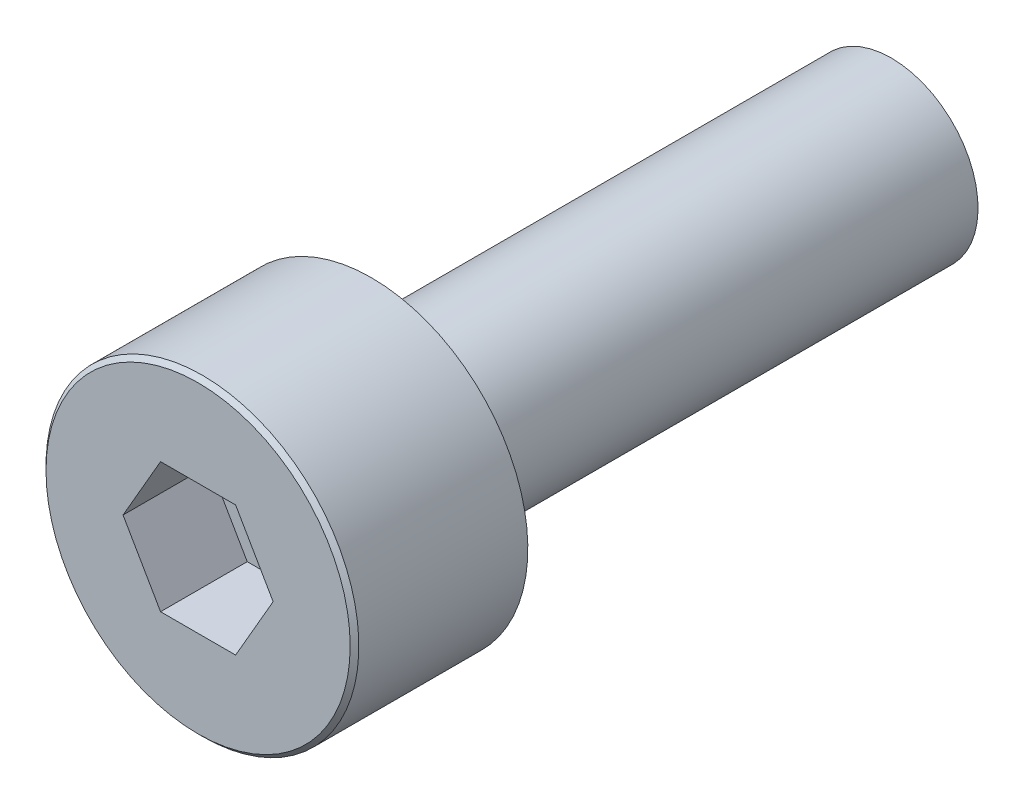
SolidWorks part; units mm, degrees
material "普通碳钢"
ref_plane "前视基准面" through (0, 0, 0) normal (0, 0, 1) x (1, 0, 0)
ref_plane "上视基准面" through (0, 0, 0) normal (0, 1, 0) x (1, 0, 0)
ref_plane "右视基准面" through (0, 0, 0) normal (1, 0, 0) x (0, 0, -1)
sketch "草图1" plane through (0, 0, 0) normal (1, 0, 0) x (0, 0, -1)
  line L0 (0, 0) -> (0, 3.61)
  line L1 (0, 3.61) -> (4, 3.61)
  line L2 (4, 3.61) -> (4, 2)
  line L3 (4, 2) -> (16, 2)
  line L4 (16, 2) -> (16, 0)
  line L5 (16, 0) -> (0, 0) construction
  line L6 (0, 0) -> (16, 0)
  dimension "D1" = 7.22
  dimension "D2" = 4
  dimension "D3" = 4
  dimension "D4" = 12
revolve "旋转1" add sketch "草图1" angle 360 about L5
cosmetic thread "装饰螺纹线1" parameters "D2"=2.459
sketch "草图2" plane through (0, 0, 0) normal (0, 0, 1) x (1, 0, 0)
  line L1 (0.866, 1.5) -> (-0.866, 1.5)
  line L2 (-0.866, 1.5) -> (-1.7321, 0)
  line L3 (-1.7321, 0) -> (-0.866, -1.5)
  line L4 (-0.866, -1.5) -> (0.866, -1.5)
  line L5 (0.866, -1.5) -> (1.7321, 0)
  line L6 (1.7321, 0) -> (0.866, 1.5)
  circle A0 centre (0, 0) radius 1.5 construction
  dimension "D1" = 3
extrude "切除-拉伸1" cut sketch "草图2" against normal blind 2
chamfer "装饰倒角" distance 0.1 angle 45 1 edges at (0, 3.61, 0)
